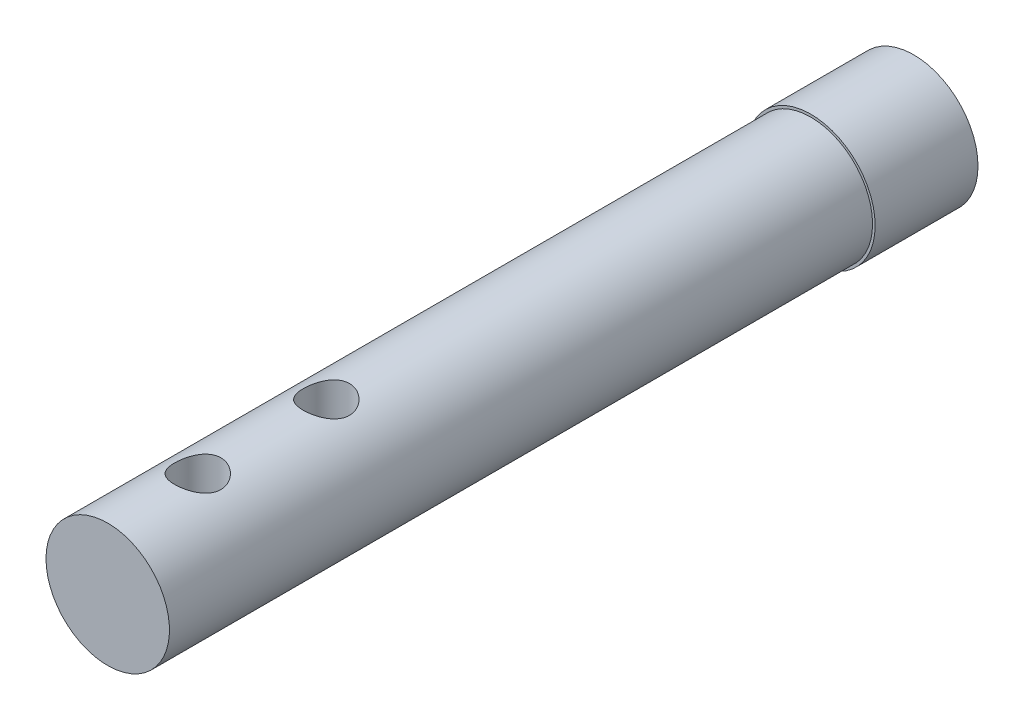
SolidWorks part; units mm, degrees
material "Galvanized Steel"
ref_plane "Front Plane" through (0, 0, 0) normal (0, 0, 1) x (1, 0, 0)
ref_plane "Top Plane" through (0, 0, 0) normal (0, 1, 0) x (1, 0, 0)
ref_plane "Right Plane" through (0, 0, 0) normal (1, 0, 0) x (0, 0, -1)
sketch "Sketch1" plane through (0, 0, 0) normal (0, 0, 1) x (1, 0, 0)
  circle A0 centre (0, 0) radius 10
  dimension "D1" = 20
extrude "Boss-Extrude1" add sketch "Sketch1" along normal blind 15
sketch "Sketch2" plane through (0, 0, 15) normal (0, 0, 1) x (1, 0, 0)
  circle A0 centre (0, 0) radius 12.5
  dimension "D1" = 25
extrude "Boss-Extrude2" add sketch "Sketch2" along normal blind 20
sketch "Sketch3" plane through (0, 0, 35) normal (0, 0, 1) x (1, 0, 0)
  circle A0 centre (0, 0) radius 12
  dimension "D1" = 24
extrude "Boss-Extrude3" add sketch "Sketch3" along normal blind 139.2
sketch "Sketch4" plane through (0, 0, 0) normal (0, 1, 0) x (1, 0, 0)
  line L0 (-12, -174.2) -> (12, -174.2) construction
  circle A0 centre (0, -154.2) radius 4.5
  dimension "D1" = 9
  dimension "D2" = 20
extrude "Cut-Extrude1" cut sketch "Sketch4" against normal through all both and the other way through all
sketch "Sketch5" plane through (0, 0, 0) normal (0, 1, 0) x (1, 0, 0)
  line L1 (12.5, -15) -> (-37.6297, -15)
  line L2 (12.5, -15) -> (12.5, 4.8742)
  line L3 (12.5, 4.8742) -> (-37.6297, 4.8742)
  line L4 (-37.6297, -15) -> (-37.6297, 4.8742)
extrude "Cut-Extrude2" cut sketch "Sketch5" against normal through all both and the other way through all
pattern_linear "LPattern1" count 2 spacing 25 along (0, 0, -1) of "Cut-Extrude1"
sketch "Sketch6" plane through (0, 0, 0) normal (0, 1, 0) x (1, 0, 0)
  line L1 (12, -174.2) -> (-15.8512, -174.2)
  line L2 (12, -174.2) -> (12, -171.7)
  line L3 (12, -171.7) -> (-15.8512, -171.7)
  line L4 (-15.8512, -174.2) -> (-15.8512, -171.7)
  line L5 (12, -174.2) -> (-15.8512, -171.7) construction
  line L6 (12, -171.7) -> (-15.8512, -174.2) construction
  point P4 (-1.9256, -172.95)
  dimension "D1" = 2.5
extrude "Cut-Extrude3" cut sketch "Sketch6" against normal through all both and the other way through all
